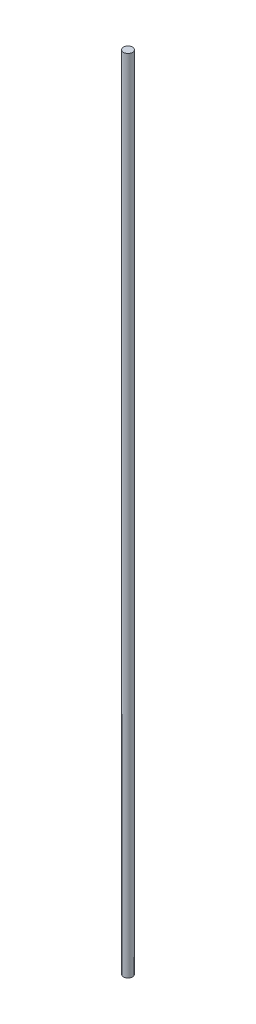
SolidWorks part; units mm, degrees
ref_plane "Plan de face" through (0, 0, 0) normal (0, 0, 1) x (1, 0, 0)
ref_plane "Plan de dessus" through (0, 0, 0) normal (0, 1, 0) x (1, 0, 0)
ref_plane "Plan de droite" through (0, 0, 0) normal (1, 0, 0) x (0, 0, -1)
sketch "Sketch1" plane through (0, 0, 0) normal (0, 1, 0) x (1, 0, 0)
  circle A0 centre (0, 0) radius 4
  dimension "D1" = 8
extrude "Boss-Extrude1" add sketch "Sketch1" along normal blind 700
